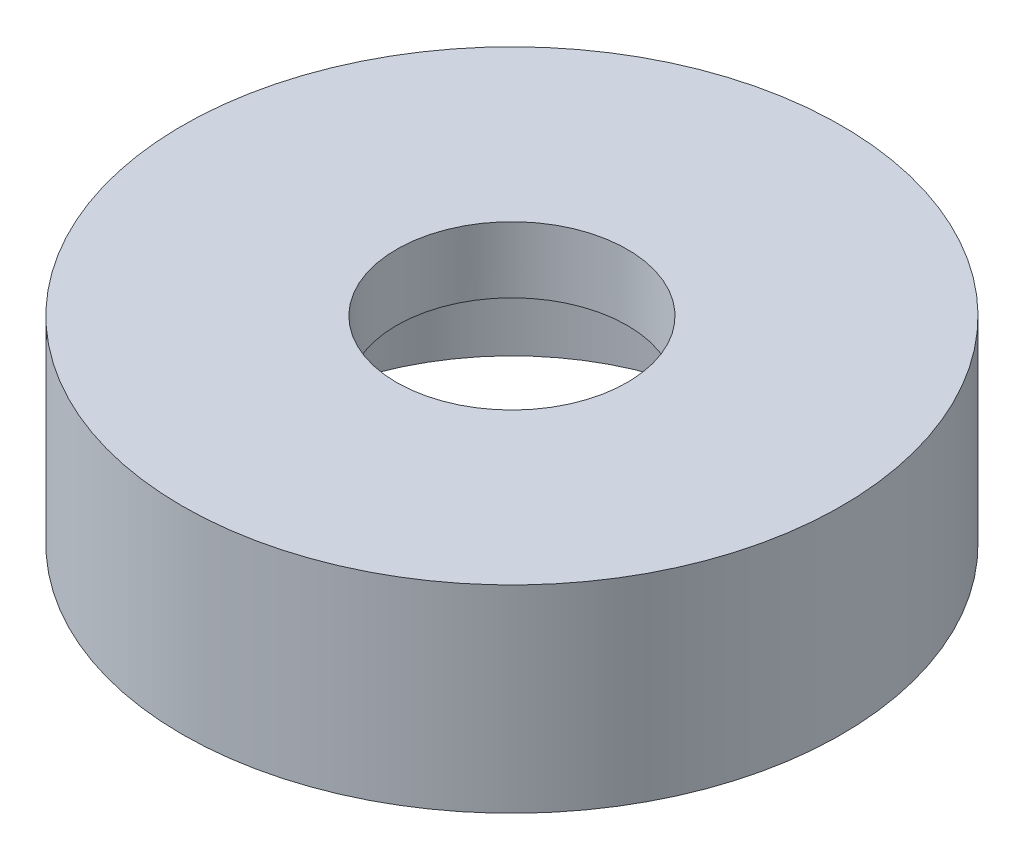
SolidWorks part; units mm, degrees
ref_plane "Спереди" through (0, 0, 0) normal (0, 0, 1) x (1, 0, 0)
ref_plane "Сверху" through (0, 0, 0) normal (0, 1, 0) x (1, 0, 0)
ref_plane "Справа" through (0, 0, 0) normal (1, 0, 0) x (0, 0, -1)
sketch "Эскиз1" plane through (0, 0, 0) normal (0, 1, 0) x (1, 0, 0)
  circle A0 centre (0, 0) radius 20
extrude "Вытянуть1" add sketch "Эскиз1" along normal blind 12
sketch "Эскиз3" plane through (0, 0, 0) normal (0, -1, 0) x (1, 0, 0)
  circle A0 centre (0, 0) radius 14
extrude "Вытянуть3" cut sketch "Эскиз3" against normal blind 8
sketch "Эскиз4" plane through (0, 12, 0) normal (0, 1, 0) x (1, 0, 0)
  circle A0 centre (0, 0) radius 7
extrude "Вытянуть4" cut sketch "Эскиз4" against normal through all
